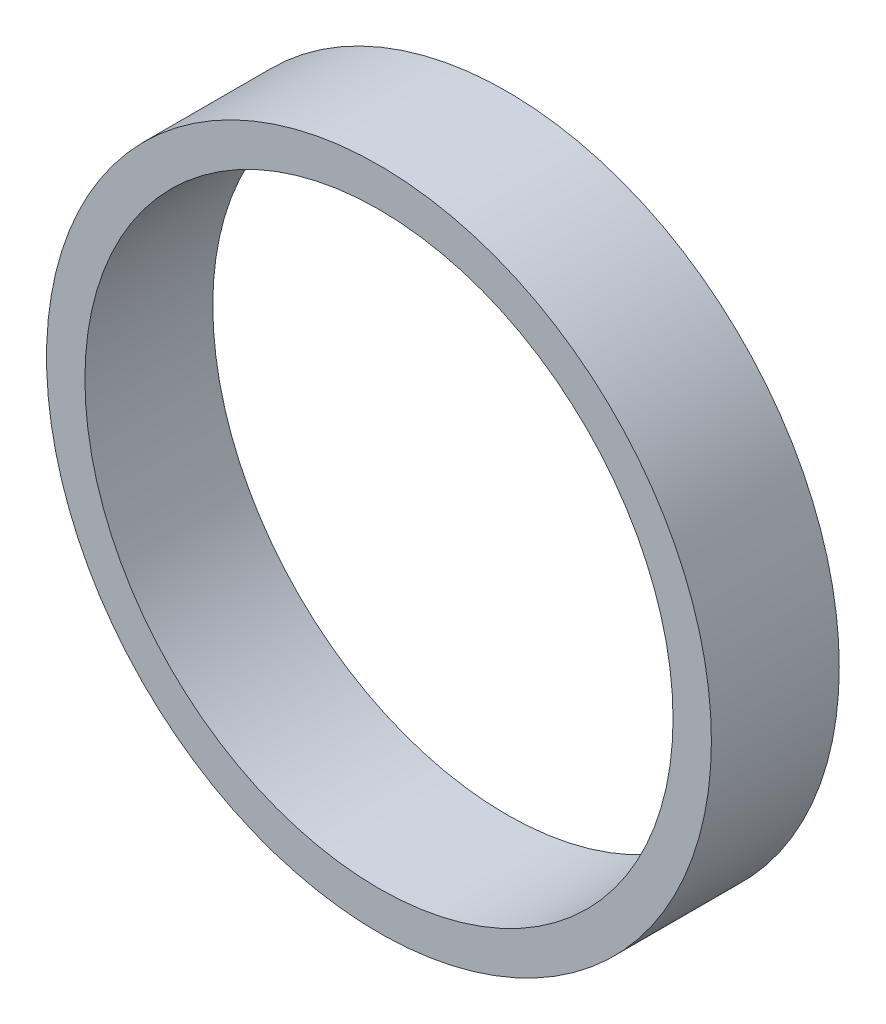
SolidWorks part; units mm, degrees
ref_plane "Płaszczyzna przednia" through (0, 0, 0) normal (0, 0, 1) x (1, 0, 0)
ref_plane "Płaszczyzna górna" through (0, 0, 0) normal (0, 1, 0) x (1, 0, 0)
ref_plane "Płaszczyzna prawa" through (0, 0, 0) normal (1, 0, 0) x (0, 0, -1)
sketch "Szkic1" plane through (0, 0, 0) normal (0, 0, 1) x (1, 0, 0)
  circle A0 centre (0, 0) radius 26
  circle A1 centre (0, 0) radius 23
  dimension "D1" = 52
  dimension "D2" = 46
extrude "Dodanie-wyciągnięcie1" add sketch "Szkic1" along normal blind 10
